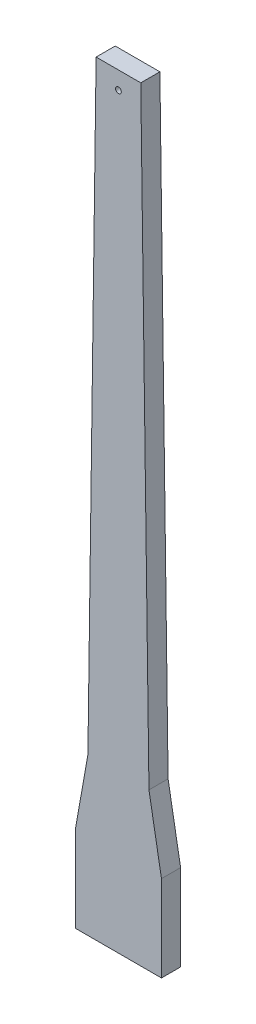
SolidWorks part; units mm, degrees
ref_plane "Front Plane" through (0, 0, 0) normal (0, 0, 1) x (1, 0, 0)
ref_plane "Top Plane" through (0, 0, 0) normal (0, 1, 0) x (1, 0, 0)
ref_plane "Right Plane" through (0, 0, 0) normal (1, 0, 0) x (0, 0, -1)
sketch "Sketch1" plane through (0, 0, 0) normal (0, 1, 0) x (1, 0, 0)
  line L1 (-19.7153, 15.3055) -> (-1.7153, 15.3055)
  line L2 (-19.7153, 15.3055) -> (-19.7153, 11.3055)
  line L3 (-19.7153, 11.3055) -> (-1.7153, 11.3055)
  line L4 (-1.7153, 15.3055) -> (-1.7153, 11.3055)
  line L5 (-19.7153, 15.3055) -> (-1.7153, 11.3055) construction
  line L6 (-19.7153, 11.3055) -> (-1.7153, 15.3055) construction
  point P0 (-10.7153, 13.3055)
extrude "Boss-Extrude1" add sketch "Sketch1" along normal blind 160
sketch "Sketch2" plane through (0, 0, 0) normal (0, 0, 1) x (1, 0, 0)
  line L0 (-19.7153, 18) -> (-19.7153, 160)
  line L1 (-19.7153, 160) -> (-19.7153, 0) construction
  line L2 (-19.7153, 18) -> (-17.1006, 32.7704)
  line L3 (-17.1006, 32.7704) -> (-15.387, 160)
  line L4 (-19.7153, 160) -> (-1.7153, 160) construction
  line L5 (-19.7153, 160) -> (-15.387, 160)
  line L7 (-4.3299, 32.7704) -> (-6.0435, 160)
  line L8 (-1.7153, 18) -> (-4.3299, 32.7704)
  line L9 (-6.0435, 160) -> (-1.7153, 160)
  line L10 (-1.7153, 160) -> (-1.7153, 18)
extrude "Cut-Extrude1" cut sketch "Sketch2" against normal blind 160
ref_plane "Plane1" through (-15.387, 160, -15.3055) normal (-1, 0, 0) x (0, 0, 1)
sketch "Sketch4" plane through (0, 0, 0) normal (0, 0, 1) x (1, 0, 0)
  circle A0 centre (-10.7153, 156.3188) radius 0.6
extrude "Cut-Extrude2" cut sketch "Sketch4" against normal blind 160
